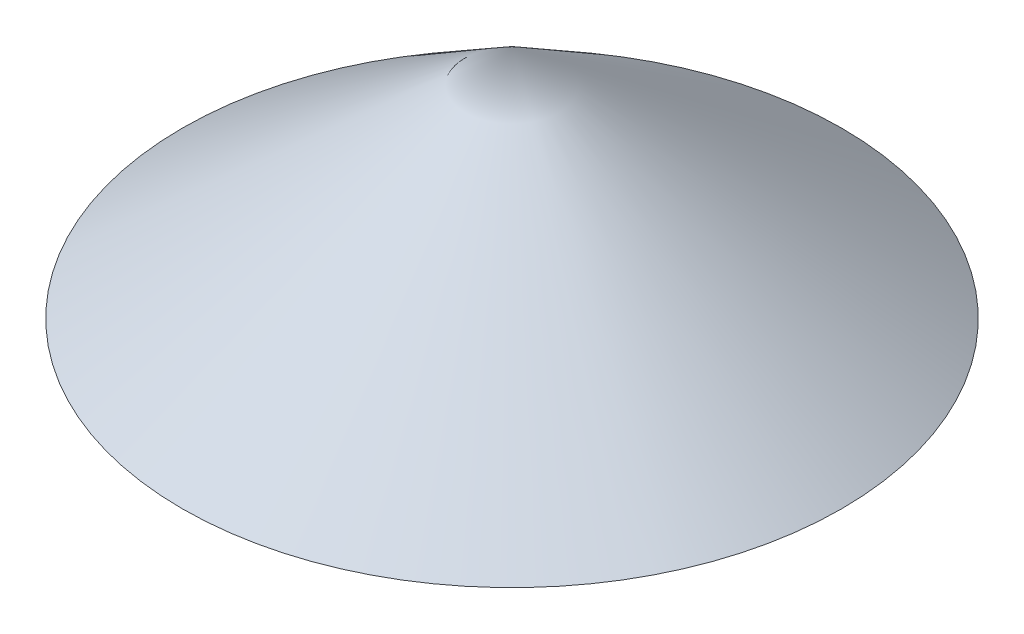
SolidWorks part; units mm, degrees
ref_plane "Front Plane" through (0, 0, 0) normal (0, 0, 1) x (1, 0, 0)
ref_plane "Top Plane" through (0, 0, 0) normal (0, 1, 0) x (1, 0, 0)
ref_plane "Right Plane" through (0, 0, 0) normal (1, 0, 0) x (0, 0, -1)
sketch "Sketch1" plane through (0, 0, 0) normal (0, 0, 1) x (1, 0, 0)
  line L0 (0, 0) -> (0, 254)
  line L1 (0, 0) -> (355.6, 0)
  line L2 (0, 254) -> (355.6, 0)
  dimension "D1" = 254
  dimension "D2" = 355.6
revolve "Revolve1" add sketch "Sketch1" angle 360 about L0
sketch "Sketch2" plane through (0, 0, 0) normal (0, 0, 1) x (1, 0, 0)
  line L0 (0, 0) -> (0, 253.365)
  line L1 (0, 0) -> (354.965, 0)
  line L2 (354.965, 0) -> (0, 253.365)
  dimension "D1" = 253.365
  dimension "D2" = 354.965
revolve "Cut-Revolve1" cut sketch "Sketch2" angle 360 about L0
